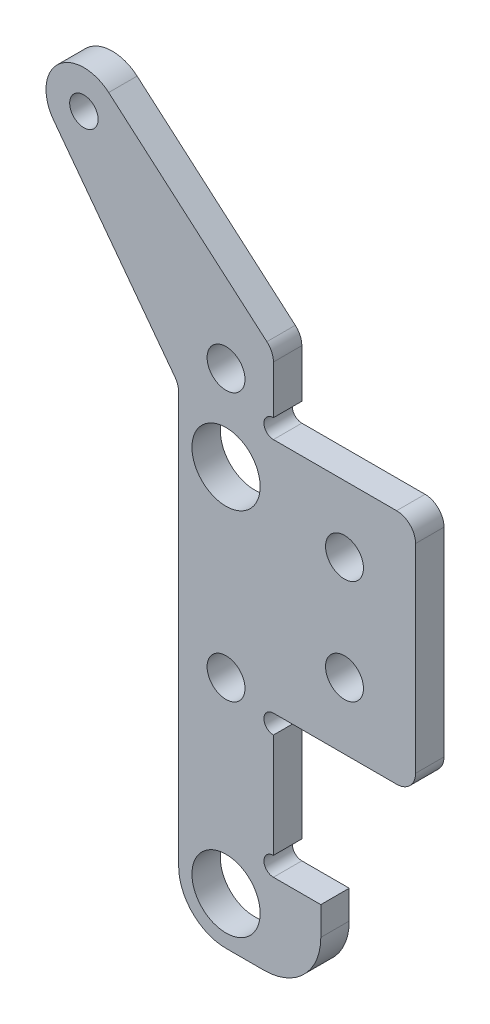
SolidWorks part; units mm, degrees
material "Thornel Mat VMA"
ref_plane "前视基准面" through (0, 0, 0) normal (0, 0, 1) x (1, 0, 0)
ref_plane "上视基准面" through (0, 0, 0) normal (0, 1, 0) x (1, 0, 0)
ref_plane "右视基准面" through (0, 0, 0) normal (1, 0, 0) x (0, 0, -1)
sketch "草图1" plane through (0, 0, 0) normal (0, 0, 1) x (1, 0, 0)
  line L0 (-63.6974, 1.3001) -> (-160.5974, 1.3001) construction
  line L1 (-188.3974, -74.6999) -> (-196.8974, -74.6999) construction
  line L3 (-188.3974, 77.3001) -> (-188.3974, -74.6999) construction
  line L5 (-160.5974, 77.3001) -> (-160.5974, -74.6999) construction
  line L6 (-152.0974, 77.3001) -> (-160.5974, 77.3001) construction
  line L7 (-152.0974, 77.3001) -> (-152.0974, -74.6999) construction
  line L8 (-152.0974, -74.6999) -> (-160.5974, -74.6999) construction
  line L9 (-196.8974, 77.3001) -> (-196.8974, -74.6999) construction
  line L10 (-188.3974, 77.3001) -> (-196.8974, 77.3001) construction
  line L11 (55, 0) -> (-55, 0) construction
  line L12 (-146.0974, 20.8001) -> (-146.0974, -18.1999)
  line L13 (-63.6974, 22.3001) -> (-134.7974, 22.3001) construction
  line L14 (-63.6974, 22.3001) -> (-63.6974, -19.6999) construction
  line L15 (-63.6974, -19.6999) -> (-134.7974, -19.6999) construction
  line L16 (-134.7974, 22.3001) -> (-134.7974, -19.6999) construction
  line L17 (-146.0974, 20.8001) -> (-60, 39)
  line L18 (-146.0974, -18.1999) -> (-60, 0)
  line L19 (-60, 0) -> (-60, 39)
  line L20 (-124.0083, -11.4863) -> (-75, 64)
  line L21 (-138, 106.5) -> (-138, 78.0686) construction
  line L22 (-75, 64) -> (27.8173, 64) construction
  line L23 (-123.5947, -13.4431) -> (-124.0083, -11.4863) construction
  circle A0 centre (-60, 0) radius 5 construction
  circle A1 centre (-60, 0) radius 3
  point P14 (-146.0974, 1.3001)
  dimension "D12" = 10
  dimension "D15" = 5
  dimension "D21" = 6
  dimension "D1" = 96.9
  dimension "D2" = 27.8
  dimension "D3" = 44.8
  dimension "D4" = 152
  dimension "D5" = 88
  dimension "D6" = 42
  dimension "D7" = 71.1
  dimension "D8" = 39
  dimension "D9" = 11.3
  dimension "D10" = 110
  dimension "D11" = 15
  dimension "D13" = 23
  dimension "D14" = 2
  dimension "D16" = 1.3001
  dimension "D17" = 138
  dimension "D18" = 64
  dimension "D20" = 90
sketch "草图7" plane through (0, 0, 0) normal (1, 0, 0) x (0, 0, -1)
  line L0 (0, 55) -> (0, -55) construction
  line L1 (-256.6842, 0) -> (256.6842, 0) construction
  line L2 (-277.7004, -107.0971) -> (-27.9153, -28.7852) construction
  line L3 (-27.9153, -28.7852) -> (291.0502, -100.0411) construction
  line L4 (-201.3277, -98.6084) -> (-65.271, -11.8548) construction
  line L5 (-65.271, -11.8548) -> (42.2558, -180.4904) construction
  line L6 (42.2558, -180.4904) -> (281.3904, -28.0114) construction
  circle A0 centre (-186, 1.3001) radius 76
  circle A1 centre (186, 1.3001) radius 76
  dimension "D1" = 152
  dimension "D2" = 186
  dimension "D3" = 150
  dimension "D4" = 200
sketch "草图2" plane through (0, 0, 0) normal (0, 0, 1) x (1, 0, 0)
  line L0 (-60, 19.75) -> (-60, 0) construction
  line L1 (-65, 0) -> (-65, 44)
  line L4 (-55, 44) -> (-40, 44)
  line L5 (-40, 44) -> (-40, 19)
  line L6 (-40, 19) -> (-55, 19)
  line L7 (-55, 19) -> (-55, 4)
  line L8 (-78.2, 61.6) -> (-65, 44)
  line L9 (-72.3843, 67.0262) -> (-55, 52)
  line L10 (-60, -5) -> (-50, -5)
  line L11 (-50, -5) -> (-50, 4)
  line L12 (-50, 4) -> (-55, 4)
  line L13 (-55, 44) -> (-55, 52)
  line L14 (-47.5, 37) -> (-47.5, 26) construction
  line L15 (-47.5, 31.5) -> (-40, 31.5) construction
  circle A0 centre (-60, 0) radius 5 construction
  arc A1 (-65, 0) -> (-60, -5) centre (-60, 0) ccw
  circle A3 centre (-60, 39) radius 3.6
  circle A4 centre (-60, 0) radius 3.6
  circle A5 centre (-75, 64) radius 1.5
  arc A6 (-72.3843, 67.0262) -> (-78.2, 61.6) centre (-75, 64) ccw
  circle A8 centre (-60, 19.75) radius 2
  circle A9 centre (-60, 48) radius 2
  circle A11 centre (-47.5, 37) radius 2
  circle A14 centre (-47.5, 26) radius 2
  dimension "D1" = 3
  dimension "D2" = 7.2
  dimension "D3" = 25
  dimension "D6" = 4
  dimension "D4" = 8
  dimension "D10" = 4
  dimension "D12" = 9
  dimension "D15" = 11
  dimension "D13" = 4
  dimension "D5" = 15
  dimension "D7" = 15
  dimension "D8" = 5
  dimension "D9" = 4
  dimension "D11" = 19.75
  dimension "D14" = 7.5
extrude "凸台-拉伸1" add sketch "草图2" along normal blind 3
sketch "草图8" plane through (0, 0, 3) normal (0, 0, 1) x (1, 0, 0)
  line L0 (-55, 44) -> (-55, 52) construction
  line L1 (-55, 4) -> (-55, 19) construction
  circle A0 centre (-55, 45) radius 1
  circle A1 centre (-55, 18) radius 1
  circle A2 centre (-55, 5) radius 1
  dimension "D1" = 2
extrude "切除-拉伸1" cut sketch "草图8" against normal through all
fillet "圆角1" radius 2 4 edges at (-55, 52, 1.5) (-65, 44, 1.5) (-40, 19, 1.5) (-40, 44, 1.5)
fillet "圆角2" radius 6 1 edges at (-50, -5, 1.5)
